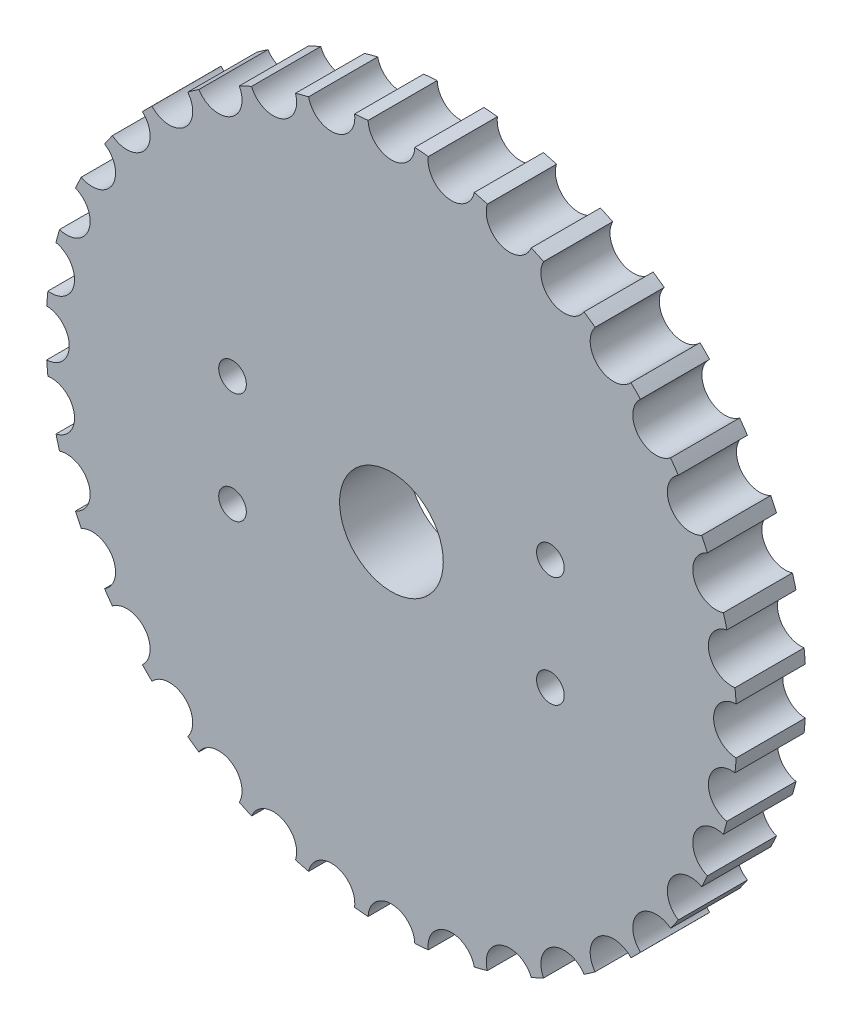
SolidWorks part; units mm, degrees
material "아크릴(내충격성)"
ref_plane "정면" through (0, 0, 0) normal (0, 0, 1) x (1, 0, 0)
ref_plane "윗면" through (0, 0, 0) normal (0, 1, 0) x (1, 0, 0)
ref_plane "우측면" through (0, 0, 0) normal (1, 0, 0) x (0, 0, -1)
sketch "스케치1" plane through (0, 0, 0) normal (0, 0, 1) x (1, 0, 0)
  circle A0 centre (0, 0) radius 50
  dimension "D1" = 100
extrude "보스-돌출1" add sketch "스케치1" along normal blind 10
sketch "스케치2" plane through (0, 0, 10) normal (0, 0, 1) x (1, 0, 0)
  line L0 (0, 0) -> (0, 53.4651) construction
  line L1 (0, 0) -> (9.1386, 52.0133) construction
  line L2 (0, 0) -> (-9.7027, 52.5525) construction
  circle A0 centre (4.373, 49.8084) radius 3.38
  circle A2 centre (0, 0) radius 50 construction
  circle A6 centre (11.6601, 43.4631) radius 3.38
  circle A7 centre (17.7347, 35.9488) radius 3.38
  circle A8 centre (22.4122, 27.4938) radius 3.38
  circle A9 centre (25.5503, 18.3551) radius 3.38
  circle A10 centre (27.0539, 8.8102) radius 3.38
  circle A11 centre (26.8772, -0.8507) radius 3.38
  circle A12 centre (25.0256, -10.3342) radius 3.38
  circle A13 centre (21.5553, -19.3521) radius 3.38
  circle A14 centre (16.5718, -27.6304) radius 3.38
  circle A15 centre (10.2265, -34.9175) radius 3.38
  circle A16 centre (2.7122, -40.9921) radius 3.38
  circle A17 centre (-5.7428, -45.6695) radius 3.38
  circle A18 centre (-14.8815, -48.8077) radius 3.38
  circle A19 centre (-24.4264, -50.3113) radius 3.38
  circle A20 centre (-34.0873, -50.1346) radius 3.38
  circle A21 centre (-43.5708, -48.283) radius 3.38
  circle A22 centre (-52.5887, -44.8127) radius 3.38
  circle A23 centre (-60.867, -39.8292) radius 3.38
  circle A24 centre (-68.1541, -33.4839) radius 3.38
  circle A25 centre (-74.2287, -25.9696) radius 3.38
  circle A26 centre (-78.9061, -17.5146) radius 3.38
  circle A27 centre (-82.0443, -8.3759) radius 3.38
  circle A28 centre (-83.5479, 1.169) radius 3.38
  circle A29 centre (-83.3712, 10.83) radius 3.38
  circle A30 centre (-81.5196, 20.3134) radius 3.38
  circle A31 centre (-78.0493, 29.3313) radius 3.38
  circle A32 centre (-73.0658, 37.6096) radius 3.38
  circle A33 centre (-66.7205, 44.8967) radius 3.38
  circle A34 centre (-59.2062, 50.9713) radius 3.38
  circle A35 centre (-50.7512, 55.6487) radius 3.38
  circle A36 centre (-41.6124, 58.7869) radius 3.38
  circle A37 centre (-32.0676, 60.2905) radius 3.38
  circle A38 centre (-22.4066, 60.1138) radius 3.38
  circle A39 centre (-12.9231, 58.2622) radius 3.38
  circle A40 centre (-3.9053, 54.7919) radius 3.38
  dimension "D1" = 106.9058
  dimension "D2" = 36
sketch "스케치4" plane through (0, 0, 10) normal (0, 0, 1) x (1, 0, 0)
  circle A0 centre (0, 0) radius 7.5
  dimension "D1" = 15
extrude "컷-돌출3" cut sketch "스케치4" against normal blind 10
sketch "스케치5" plane through (0, 0, 10) normal (0, 0, 1) x (1, 0, 0)
  line L0 (-52.1074, 0) -> (52.2141, 0) construction
  line L1 (-52.1074, -15) -> (52.2141, -15)
  line L2 (-52.1074, 15) -> (52.2141, 15)
  line L3 (0, 53.1222) -> (0, -55.2945) construction
  line L4 (-30, 53.1222) -> (-30, -55.2945)
  line L5 (30, 53.1222) -> (30, -55.2945)
  circle A0 centre (-23, 8) radius 2
  circle A1 centre (23, 8) radius 2
  circle A2 centre (23, -8) radius 2
  circle A3 centre (-23, -8) radius 2
  dimension "D5" = 4
  dimension "D7" = 7
  dimension "D6" = 7
  dimension "D1" = 15
  dimension "D2" = 15
  dimension "D3" = 30
  dimension "D4" = 30
extrude "컷-돌출4" cut sketch "스케치5" against normal blind 10 contours A3 | A0 | A1 | A2
sketch "스케치6" plane through (0, 0, 10) normal (0, 0, 1) x (1, 0, 0)
  line L0 (0, 0) -> (0, 53.4651) construction
  circle A0 centre (0, 50) radius 3.38
  circle A1 centre (0, 0) radius 50 construction
  circle A2 centre (8.6824, 49.2404) radius 3.38
  circle A3 centre (17.101, 46.9846) radius 3.38
  circle A4 centre (25, 43.3013) radius 3.38
  circle A5 centre (32.1394, 38.3022) radius 3.38
  circle A6 centre (38.3022, 32.1394) radius 3.38
  circle A7 centre (43.3013, 25) radius 3.38
  circle A8 centre (46.9846, 17.101) radius 3.38
  circle A9 centre (49.2404, 8.6824) radius 3.38
  circle A10 centre (50, 0) radius 3.38
  circle A11 centre (49.2404, -8.6824) radius 3.38
  circle A12 centre (46.9846, -17.101) radius 3.38
  circle A13 centre (43.3013, -25) radius 3.38
  circle A14 centre (38.3022, -32.1394) radius 3.38
  circle A15 centre (32.1394, -38.3022) radius 3.38
  circle A16 centre (25, -43.3013) radius 3.38
  circle A17 centre (17.101, -46.9846) radius 3.38
  circle A18 centre (8.6824, -49.2404) radius 3.38
  circle A19 centre (0, -50) radius 3.38
  circle A20 centre (-8.6824, -49.2404) radius 3.38
  circle A21 centre (-17.101, -46.9846) radius 3.38
  circle A22 centre (-25, -43.3013) radius 3.38
  circle A23 centre (-32.1394, -38.3022) radius 3.38
  circle A24 centre (-38.3022, -32.1394) radius 3.38
  circle A25 centre (-43.3013, -25) radius 3.38
  circle A26 centre (-46.9846, -17.101) radius 3.38
  circle A27 centre (-49.2404, -8.6824) radius 3.38
  circle A28 centre (-50, 0) radius 3.38
  circle A29 centre (-49.2404, 8.6824) radius 3.38
  circle A30 centre (-46.9846, 17.101) radius 3.38
  circle A31 centre (-43.3013, 25) radius 3.38
  circle A32 centre (-38.3022, 32.1394) radius 3.38
  circle A33 centre (-32.1394, 38.3022) radius 3.38
  circle A34 centre (-25, 43.3013) radius 3.38
  circle A35 centre (-17.101, 46.9846) radius 3.38
  circle A36 centre (-8.6824, 49.2404) radius 3.38
  point P79 (0, 0)
  dimension "D1" = 36
extrude "컷-돌출5" cut sketch "스케치6" against normal through all
